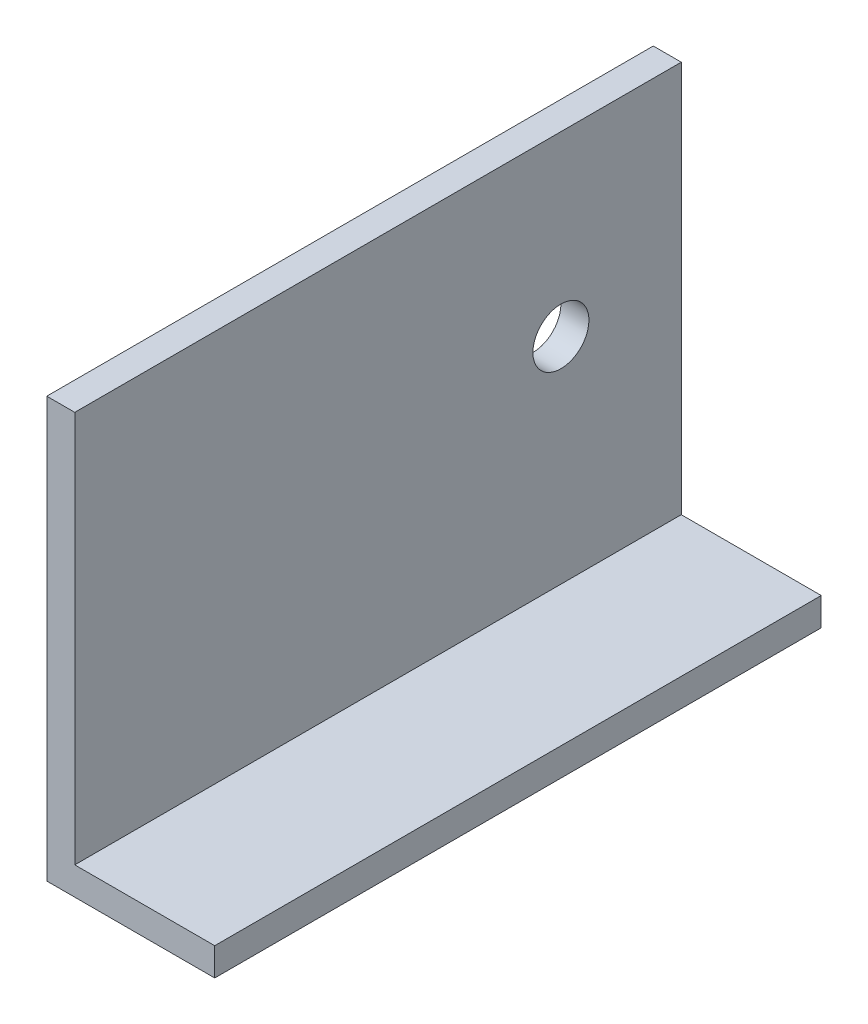
SolidWorks part; units mm, degrees
ref_plane "前视基准面" through (0, 0, 0) normal (0, 0, 1) x (1, 0, 0)
ref_plane "上视基准面" through (0, 0, 0) normal (0, 1, 0) x (1, 0, 0)
ref_plane "右视基准面" through (0, 0, 0) normal (1, 0, 0) x (0, 0, -1)
other "Configuration Table"
sketch "草图1" plane through (0, 0, 0) normal (0, 0, 1) x (1, 0, 0)
  line L1 (0, 45) -> (3, 45)
  line L2 (0, 45) -> (0, 0)
  line L3 (0, 0) -> (3, 0)
  line L4 (3, 45) -> (3, 0)
  line L5 (3, 3) -> (18, 3)
  line L6 (3, 3) -> (3, 0)
  line L7 (3, 0) -> (18, 0)
  line L8 (18, 3) -> (18, 0)
  dimension "D1" = 3
  dimension "D2" = 45
  dimension "D3" = 15
  dimension "D4" = 3
extrude "凸台-拉伸1" add sketch "草图1" along normal blind 65 contours L4 L1 L2 L3 | L6 L5 L8 L7
sketch "草图2" plane through (3, 0, 0) normal (1, 0, 0) x (0, 0, -1)
  line L0 (-65, 45) -> (-65, 3) construction
  line L2 (-65, 45) -> (0, 45) construction
  circle A0 centre (-12.9, 26) radius 3
  dimension "D1" = 6
  dimension "D2" = 52.1
  dimension "D3" = 19
extrude "切除-拉伸1" cut sketch "草图2" against normal blind 64.5
